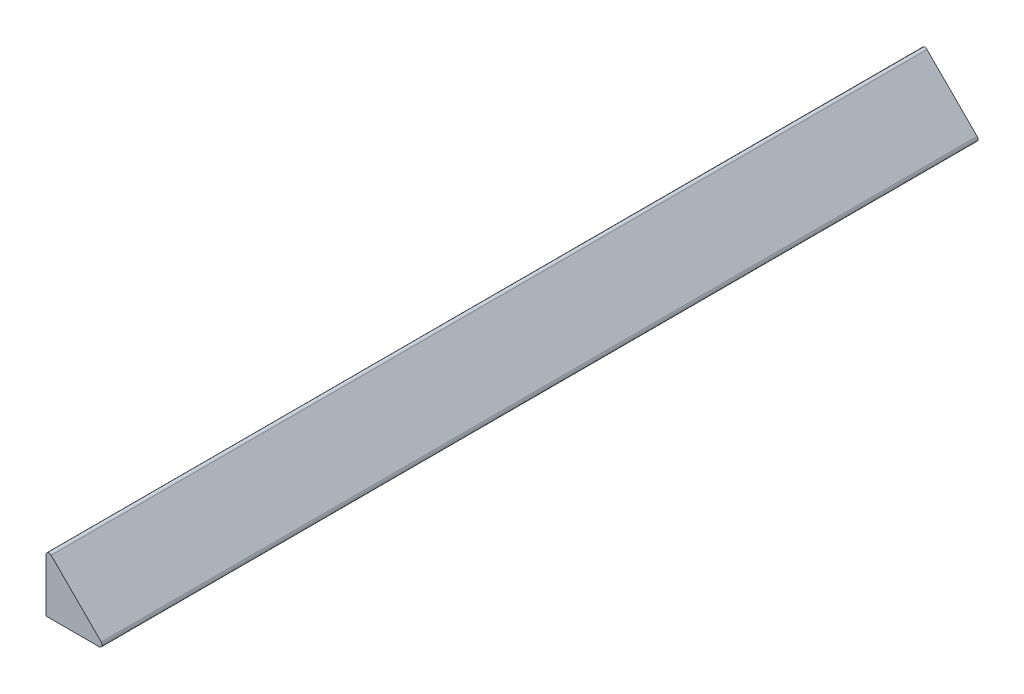
SolidWorks part; units mm, degrees
ref_plane "Спереди" through (0, 0, 0) normal (0, 0, 1) x (1, 0, 0)
ref_plane "Сверху" through (0, 0, 0) normal (0, 1, 0) x (1, 0, 0)
ref_plane "Справа" through (0, 0, 0) normal (1, 0, 0) x (0, 0, -1)
sketch "Эскиз1" plane through (0, 0, 0) normal (0, 0, 1) x (1, 0, 0)
  line L0 (0, 0) -> (0, 20)
  line L1 (0, 20) -> (20, 0)
  line L2 (20, 0) -> (0, 0)
  dimension "D1" = 20
  dimension "D2" = 20
extrude "Бобышка-Вытянуть1" add sketch "Эскиз1" against normal blind 290
fillet "Скругление1" radius 1 2 edges at (0, 20, -145) (20, 0, -145)
